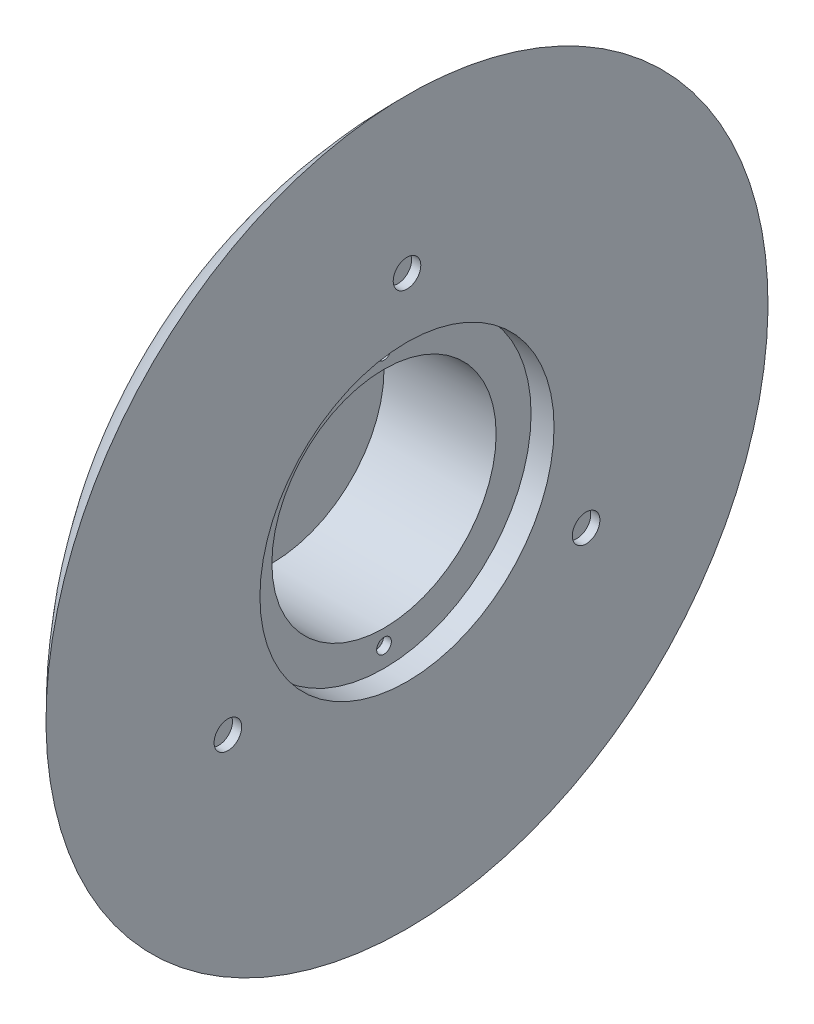
SolidWorks part; units mm, degrees
material "铸造合金钢"
ref_plane "前视基准面" through (0, 0, 0) normal (0, 0, 1) x (1, 0, 0)
ref_plane "上视基准面" through (0, 0, 0) normal (0, 1, 0) x (1, 0, 0)
ref_plane "右视基准面" through (0, 0, 0) normal (1, 0, 0) x (0, 0, -1)
sketch "草图1" plane through (0, 0, 0) normal (0, 0, 1) x (1, 0, 0)
  line L0 (0, 0) -> (0, -55) construction
  line L1 (0, 55) -> (0, -55)
  line L2 (-38.5, 39.2779) -> (-38.5, -39.2779)
  line L3 (0, 0) -> (-55, 0)
  arc A0 (0, 55) -> (0, -55) centre (0, 0) ccw
  dimension "D1" = 110
  dimension "D2" = 38.5
revolve "旋转4" add sketch "草图1" angle 360 about L1
sketch "草图2" plane through (0, 0, 0) normal (0, 0, 1) x (1, 0, 0)
  line L0 (0, 0) -> (0, 55)
  line L1 (0, 55) -> (-38.5, 55)
  line L2 (-38.5, 55) -> (-38.5, -53.3286)
  line L3 (-38.5, -53.3286) -> (-38.5, -63.8902)
  line L4 (-38.5, -63.8902) -> (57.7444, -63.8902)
  line L5 (57.7444, -63.8902) -> (57.7444, 55)
  line L6 (57.7444, 55) -> (0, 55)
  circle A0 centre (0, 0) radius 55 construction
  dimension "D1" = 38.5
extrude "切除-拉伸1" cut sketch "草图2" against normal through all and the other way through all
sketch "草图3" plane through (-38.5, 0, 0) normal (1, 0, 0) x (0, 0, -1)
  circle A0 centre (0, 0) radius 12.2
  dimension "D1" = 24.4
extrude "切除-拉伸2" cut sketch "草图3" against normal blind 14.7
sketch "草图4" plane through (-53.2, 0, 0) normal (1, 0, 0) x (0, 0, -1)
  circle A0 centre (0, 0) radius 3
  dimension "D1" = 6
extrude "切除-拉伸3" cut sketch "草图4" against normal blind 0.7
sketch "草图5" plane through (-38.5, 0, 0) normal (1, 0, 0) x (0, 0, -1)
  circle A0 centre (0, 0) radius 22.5 construction
  circle A1 centre (0, 22.5) radius 1.5
  circle A2 centre (19.4856, -11.25) radius 1.5
  circle A3 centre (-19.4856, -11.25) radius 1.5
  point P11 (0, 0)
  dimension "D1" = 45
  dimension "D2" = 3
  dimension "D3" = 3
extrude "凸台-拉伸1" add sketch "草图5" along normal blind 1
sketch "草图6" plane through (-37.5, 0, 0) normal (1, 0, 0) x (0, 0, -1)
  circle A0 centre (0, 22.5) radius 1.5
  circle A1 centre (-19.4856, -11.25) radius 1.5
  circle A2 centre (19.4856, -11.25) radius 1.5
extrude "切除-拉伸4" cut sketch "草图6" against normal blind 2
sketch "草图7" plane through (-38.5, 0, 0) normal (1, 0, 0) x (0, 0, -1)
  circle A0 centre (0, 0) radius 16
extrude "切除-拉伸5" cut sketch "草图7" against normal blind 2.5
sketch "草图8" plane through (-41, 0, 0) normal (1, 0, 0) x (0, 0, -1)
  circle A0 centre (0, 14.008) radius 1.5982
  circle A1 centre (0, -14.008) radius 1.5982
extrude "切除-拉伸6" cut sketch "草图8" against normal blind 1.33
sketch "草图9" plane through (-41, 0, 0) normal (1, 0, 0) x (0, 0, -1)
  circle A0 centre (0, 14.008) radius 0.8
  circle A1 centre (0, -14.008) radius 0.8
extrude "切除-拉伸9" cut sketch "草图9" against normal blind 1.98
sketch "草图13" plane through (-42.98, 0, 0) normal (1, 0, 0) x (0, 0, -1)
  circle A0 centre (0, 14.008) radius 0.8
extrude "凸台-拉伸2" add sketch "草图13" along normal blind 1.98
sketch "草图15" plane through (-42.33, 0, 0) normal (1, 0, 0) x (0, 0, -1)
  circle A0 centre (0, 14.008) radius 1.5982
extrude "凸台-拉伸3" add sketch "草图15" along normal blind 1.33
sketch "草图16" plane through (-42.33, 0, 0) normal (1, 0, 0) x (0, 0, -1)
  circle A0 centre (0, -14.008) radius 1.5982
sketch "草图18" plane through (-42.98, 0, 0) normal (1, 0, 0) x (0, 0, -1)
  circle A0 centre (0, -14.008) radius 0.8
extrude "凸台-拉伸5" add sketch "草图18" along normal blind 1.98
extrude "凸台-拉伸6" add sketch "草图16" along normal blind 1.33 contours A0
sketch "草图19" plane through (-41, 0, 0) normal (1, 0, 0) x (0, 0, -1)
  circle A0 centre (0, 13.8504) radius 0.4
extrude "切除-拉伸10" cut sketch "草图19" against normal blind 1.98
sketch "草图21" plane through (-42.98, 0, 0) normal (1, 0, 0) x (0, 0, -1)
  circle A0 centre (0, 13.8504) radius 0.4
  circle A1 centre (0, -13.8504) radius 0.4
extrude "切除-拉伸13" cut sketch "草图21" along normal blind 1.98
sketch "草图22" plane through (-41, 0, 0) normal (1, 0, 0) x (0, 0, -1)
  line L0 (0, 0) -> (1.7427, 0)
  circle A0 centre (0, 13.8504) radius 0.8
  circle A1 centre (0, -13.8504) radius 0.8
extrude "切除-拉伸14" cut sketch "草图22" against normal blind 1.33 contours A0 | A1
sketch "草图24" plane through (-42.98, 0, 0) normal (1, 0, 0) x (0, 0, -1)
  circle A0 centre (0, 13.8504) radius 0.4
  circle A1 centre (0, -13.8504) radius 0.4
extrude "凸台-拉伸8" add sketch "草图24" along normal blind 0.47
sketch "草图25" plane through (-42.33, 0, 0) normal (1, 0, 0) x (0, 0, -1)
  circle A0 centre (0, 13.8504) radius 0.8
  circle A1 centre (0, -13.8504) radius 0.8
  circle A2 centre (0, 13.8504) radius 0.4
  circle A3 centre (0, -13.8504) radius 0.4
extrude "凸台-拉伸10" add sketch "草图25" along normal blind 0.47
